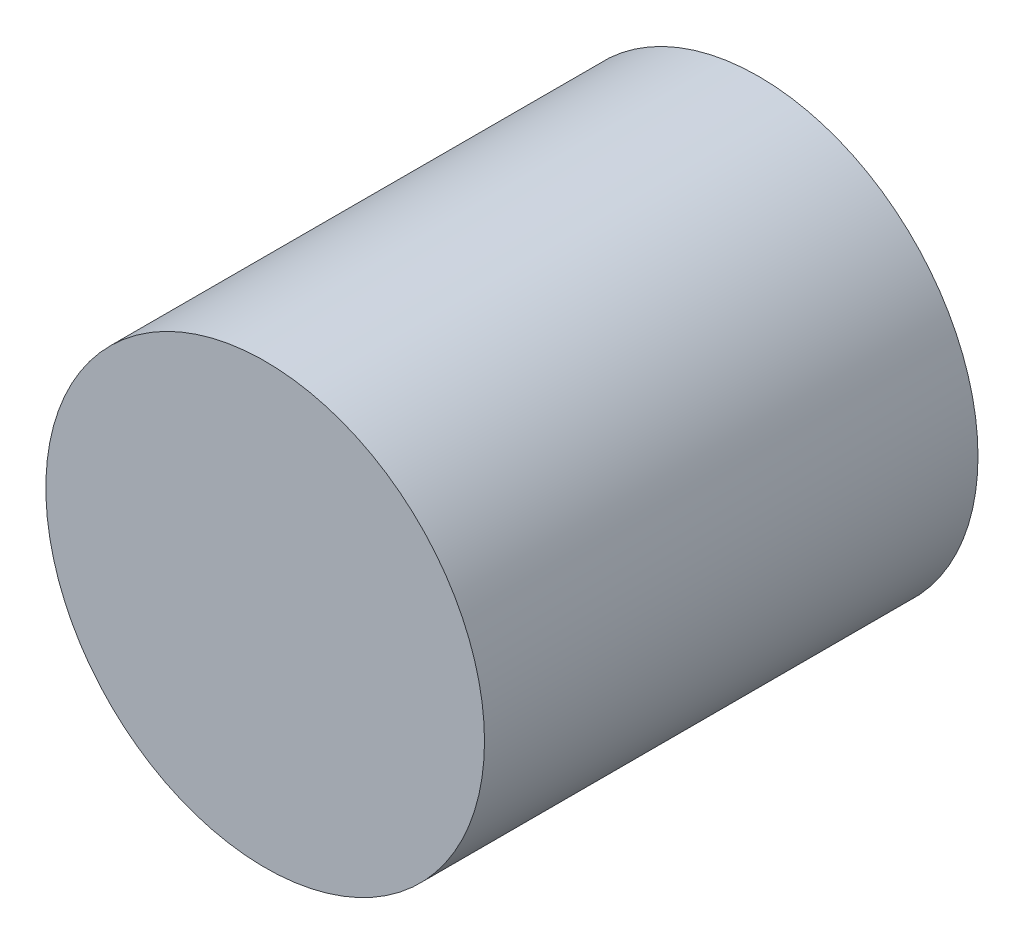
SolidWorks part; units mm, degrees
ref_plane "Plane1" through (0, 0, 0) normal (0, 0, 1) x (1, 0, 0)
ref_plane "Plane2" through (0, 0, 0) normal (0, 1, 0) x (1, 0, 0)
ref_plane "Plane3" through (0, 0, 0) normal (1, 0, 0) x (0, 0, -1)
sketch "Sketch1" plane through (0, 0, 0) normal (0, 0, 1) x (1, 0, 0)
  circle A0 centre (425, -70) radius 20 construction
  circle A1 centre (425, -70) radius 20
extrude "Extrude1" add sketch "Sketch1" against normal up to surface (45 mm away)
